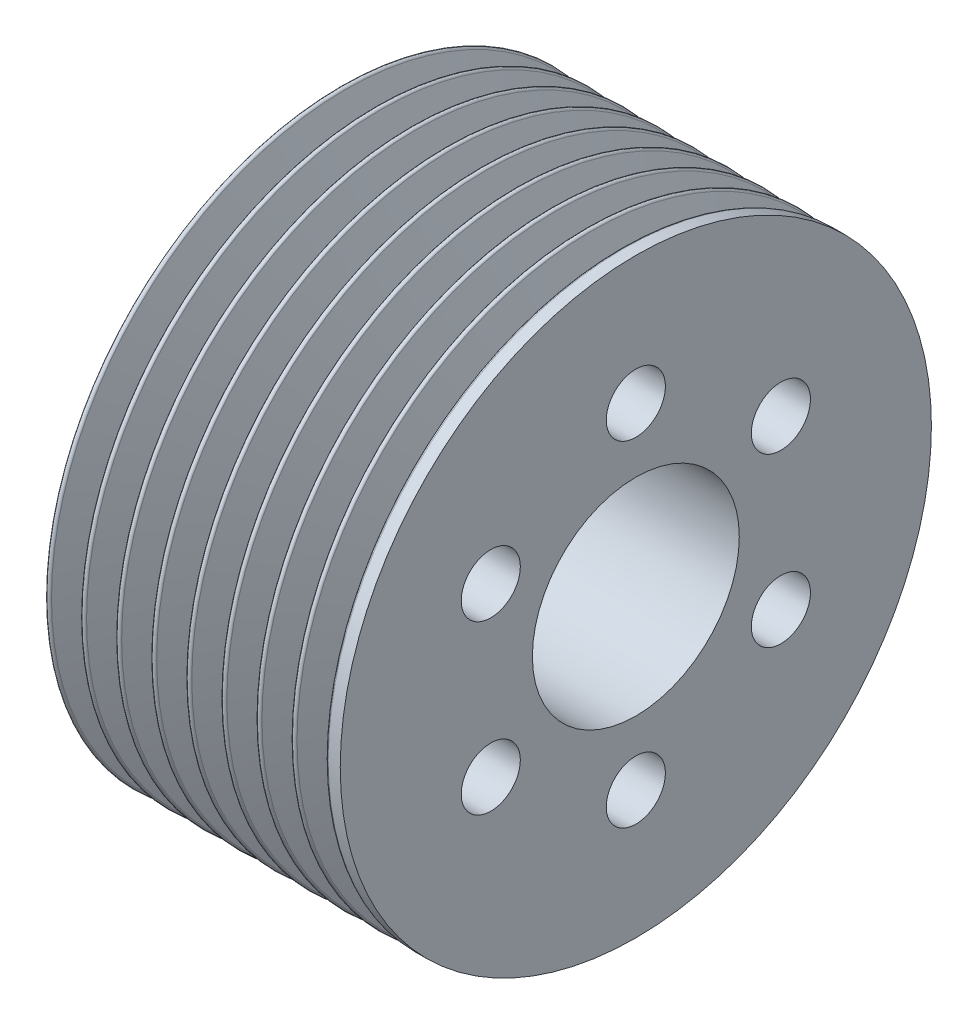
SolidWorks part; units mm, degrees
material "2018 Alloy"
ref_plane "Front Plane" through (0, 0, 0) normal (0, 0, 1) x (1, 0, 0)
ref_plane "Top Plane" through (0, 0, 0) normal (0, 1, 0) x (1, 0, 0)
ref_plane "Right Plane" through (0, 0, 0) normal (1, 0, 0) x (0, 0, -1)
sketch "Sketch1" plane through (0, 0, 0) normal (0, 0, 1) x (1, 0, 0)
  line L0 (49, 10.5) -> (49, 0) construction
  line L1 (49, 10.5) -> (49, 30)
  line L2 (49, 30) -> (18, 30)
  line L3 (18, 30) -> (18, 21.5)
  line L4 (49, 10.5) -> (31.5, 10.5)
  line L5 (0, 0) -> (49, 0) construction
  line L6 (18, 21.5) -> (31.5, 21.5)
  line L8 (0, 8.3175) -> (0, 0) construction
  line L9 (31.5, 10.5) -> (31.5, 21.5)
  dimension "D1" = 31
  dimension "D2" = 60
  dimension "D3" = 31.5
  dimension "D4" = 43
  dimension "D5" = 49
  dimension "D8" = 21
revolve "Revolve1" add sketch "Sketch1" angle 360 about L5
sketch "Sketch2" plane through (0, 0, 0) normal (0, 0, 1) x (1, 0, 0)
  line L0 (47.5458, 29.8376) -> (46.281, 26.4546)
  line L1 (45.719, 26.4546) -> (44.4542, 29.8376)
  line L2 (47.5458, 29.8376) -> (47.6066, 30) construction
  line L3 (49, 30) -> (18, 30) construction
  line L4 (44.4542, 29.8376) -> (44.3934, 30) construction
  line L5 (49, -30) -> (49, 30) construction
  line L6 (47.78, 30) -> (44.22, 30)
  line L7 (0, 0) -> (49, 0) construction
  arc A0 (47.5458, 29.8376) -> (47.78, 30) centre (47.78, 29.75) cw
  arc A1 (44.4542, 29.8376) -> (44.22, 30) centre (44.22, 29.75) ccw
  arc A2 (46.281, 26.4546) -> (45.719, 26.4546) centre (46, 26.5597) cw
  dimension "D2" = 0.25
  dimension "D3" = 0.3
  dimension "D1" = 41
  dimension "D4" = 3.56
  dimension "D5" = 3
revolve "Cut-Revolve1" cut sketch "Sketch2" angle 360 about L7
pattern_linear "LPattern1" count 9 spacing 3.56 along (-1, 0, 0) of "Cut-Revolve1"
sketch "Sketch3" plane through (49, 0, 0) normal (1, 0, 0) x (0, 0, -1)
  circle A0 centre (0, 0) radius 17 construction
  circle A1 centre (0, 17) radius 3
  circle A2 centre (14.7224, 8.5) radius 3
  circle A3 centre (14.7224, -8.5) radius 3
  circle A4 centre (0, -17) radius 3
  circle A5 centre (-14.7224, -8.5) radius 3
  circle A6 centre (-14.7224, 8.5) radius 3
  dimension "D1" = 34
  dimension "D2" = 6
  dimension "D3" = 6
extrude "Cut-Extrude1" cut sketch "Sketch3" against normal up to surface (17.5 mm away) up to face at (31.5, 0, 10.5)
